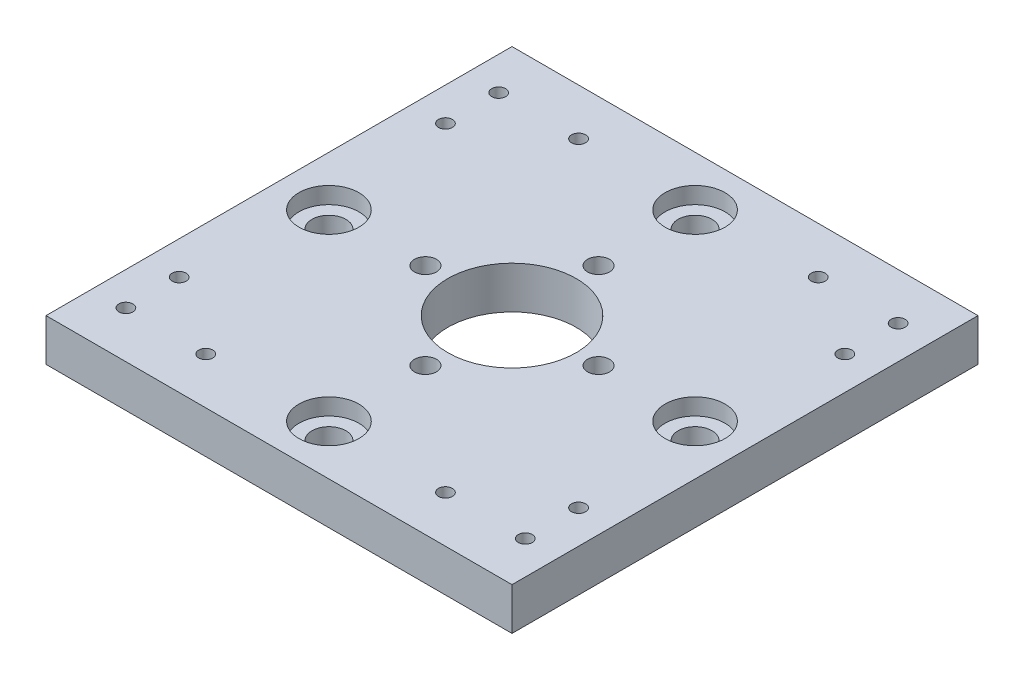
SolidWorks part; units mm, degrees
ref_plane "Front Plane" through (0, 0, 0) normal (0, 0, 1) x (1, 0, 0)
ref_plane "Top Plane" through (0, 0, 0) normal (0, 1, 0) x (1, 0, 0)
ref_plane "Right Plane" through (0, 0, 0) normal (1, 0, 0) x (0, 0, -1)
sketch "Sketch1" plane through (0, 0, 0) normal (0, 1, 0) x (1, 0, 0)
  line L1 (-35, -35) -> (35, -35)
  line L2 (-35, -35) -> (-35, 35)
  line L3 (-35, 35) -> (35, 35)
  line L4 (35, -35) -> (35, 35)
  line L5 (-35, -35) -> (35, 35) construction
  line L6 (-35, 35) -> (35, -35) construction
  circle A1 centre (0, 0) radius 13
  circle A2 centre (0, 13) radius 1.65
  circle A3 centre (13, 0) radius 1.65
  circle A4 centre (0, -13) radius 1.65
  circle A5 centre (-13, 0) radius 1.65
  point P1 (0, 0)
  point P16 (-4.3848, 11.2041)
  point P17 (0, 0)
  dimension "D1" = 26
  dimension "D2" = 3.3
  dimension "D3" = 70
  dimension "D4" = 70
extrude "Boss-Extrude1" add sketch "Sketch1" along normal blind 6.35
sketch "Sketch2" plane through (0, 6.35, 0) normal (0, 1, 0) x (1, 0, 0)
  line L0 (0, 0) -> (0, 50000) construction
  line L1 (0, 0) -> (-50000, 0) construction
  circle A0 centre (18, 28) radius 1.05
  circle A1 centre (30, 28) radius 1.05
  circle A2 centre (30, 20) radius 1.05
  circle A3 centre (-30, 20) radius 1.05
  circle A4 centre (-30, 28) radius 1.05
  circle A5 centre (-18, 28) radius 1.05
  circle A6 centre (30, -20) radius 1.05
  circle A7 centre (30, -28) radius 1.05
  circle A8 centre (18, -28) radius 1.05
  circle A9 centre (-18, -28) radius 1.05
  circle A10 centre (-30, -20) radius 1.05
  circle A11 centre (-30, -28) radius 1.05
  dimension "D1" = 2.1
  dimension "D2" = 8
  dimension "D3" = 12
  dimension "D4" = 20
  dimension "D5" = 30
extrude "Cut-Extrude1" cut sketch "Sketch2" against normal up to next
sketch "Sketch3" plane through (0, 6.35, 0) normal (0, 1, 0) x (1, 0, 0)
  circle A0 centre (0, 0) radius 9.65
  dimension "D1" = 19.3
extrude "Cut-Extrude2" cut sketch "Sketch3" against normal up to next
sketch "Sketch4" plane through (0, 6.35, 0) normal (0, 1, 0) x (1, 0, 0)
  circle A0 centre (0, 0) radius 27.5
  circle A1 centre (0, 27.5) radius 2.55
  circle A2 centre (27.5, 0) radius 2.55
  circle A3 centre (0, -27.5) radius 2.55
  circle A4 centre (-27.5, 0) radius 2.55
  point P13 (0, 0)
  dimension "D1" = 55
  dimension "D2" = 5.1
  dimension "D3" = 4
extrude "Cut-Extrude3" cut sketch "Sketch4" against normal up to next contours A0 A4 | A0 A4 | A0 A1 | A0 A1 | A0 A2 | A0 A2 | A0 A3 | A0 A3
sketch "Sketch5" plane through (0, 6.35, 0) normal (0, 1, 0) x (1, 0, 0)
  circle A0 centre (0, 27.5) radius 4.5
  circle A1 centre (27.5, 0) radius 4.5
  circle A2 centre (0, -27.5) radius 4.5
  circle A3 centre (-27.5, 0) radius 4.5
  dimension "D1" = 9
extrude "Cut-Extrude4" cut sketch "Sketch5" against normal blind 2.5
